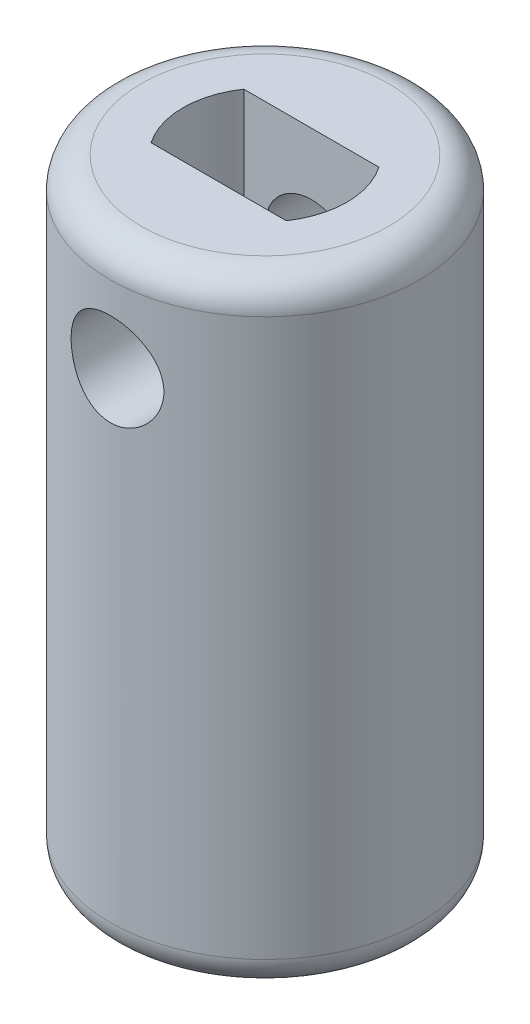
SolidWorks part; units mm, degrees
ref_plane "Alzado" through (0, 0, 0) normal (0, 0, 1) x (1, 0, 0)
ref_plane "Planta" through (0, 0, 0) normal (0, 1, 0) x (1, 0, 0)
ref_plane "Vista lateral" through (0, 0, 0) normal (1, 0, 0) x (0, 0, -1)
sketch "Croquis1" plane through (0, 0, 0) normal (0, 1, 0) x (1, 0, 0)
  circle A0 centre (0, 0) radius 5
  dimension "D1" = 10
extrude "Saliente-Extruir1" add sketch "Croquis1" along normal blind 20
sketch "Croquis2" plane through (0, 20, 0) normal (0, 1, 0) x (1, 0, 0)
  line L0 (0, 0) -> (0, 1.5) construction
  line L1 (0, 1.5) -> (0, -1.5) construction
  line L2 (0, 1.5) -> (-2.1846, 1.5)
  line L3 (-2.1846, 1.5) -> (2.1846, 1.5)
  line L4 (0, -1.5) -> (-2.1846, -1.5)
  line L5 (-2.1846, -1.5) -> (2.1846, -1.5)
  circle A0 centre (0, 0) radius 2.65
  dimension "D1" = 5.3
  dimension "D2" = 1.5
  dimension "D3" = 1.5
extrude "Cortar-Extruir1" cut sketch "Croquis2" against normal blind 7 contours L5 A0 L3 L2 L4
sketch "Croquis3" plane through (0, 0, -1.5) normal (0, 0, 1) x (1, 0, 0)
  line L0 (-2.1846, 20) -> (2.1846, 20) construction
  line L1 (2.1846, 13) -> (2.1846, 20) construction
  circle A0 centre (0, 16.5) radius 1.5
  dimension "D1" = 3
  dimension "D2" = 3.5
  dimension "D3" = 2.1846
extrude "Cortar-Extruir2" cut sketch "Croquis3" along normal through all and the other way through all
sketch "Croquis4" plane through (0, 0, 0) normal (0, -1, 0) x (1, 0, 0)
  circle A0 centre (0, 0) radius 3.175
  dimension "D1" = 6.35
extrude "Cortar-Extruir3" cut sketch "Croquis4" against normal blind 13
fillet "Redondeo1" radius 1 2 edges at (0, 20, 5) (0, 0, 5)
